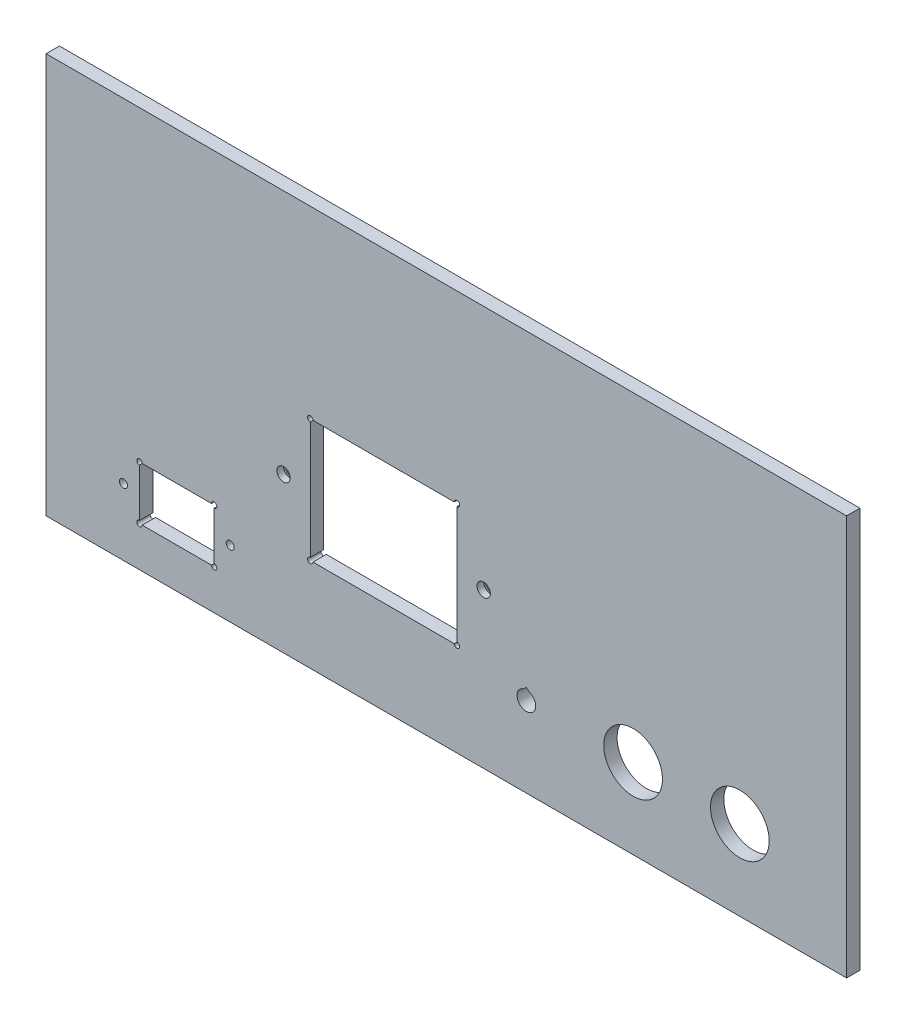
SolidWorks part; units mm, degrees
material "Glas"
ref_plane "Ebene vorne" through (0, 0, 0) normal (0, 0, 1) x (1, 0, 0)
ref_plane "Ebene oben" through (0, 0, 0) normal (0, 1, 0) x (1, 0, 0)
ref_plane "Ebene rechts" through (0, 0, 0) normal (1, 0, 0) x (0, 0, -1)
sketch "Skizze1" plane through (0, 0, 0) normal (0, 0, 1) x (1, 0, 0)
  line L1 (-150, 75) -> (150, 75)
  line L2 (-150, 75) -> (-150, -75)
  line L3 (-150, -75) -> (150, -75)
  line L4 (150, 75) -> (150, -75)
  line L5 (-150, 75) -> (150, -75) construction
  line L6 (-150, -75) -> (150, 75) construction
  point P0 (0, 0)
  dimension "D1" = 300
  dimension "D2" = 150
extrude "Aufsatz-Linear austragen1" add sketch "Skizze1" along normal blind 5
sketch "Skizze2" plane through (0, 0, 5) normal (0, 0, 1) x (1, 0, 0)
  line L0 (-150, 75) -> (-150, -75) construction
  line L1 (-115, -40) -> (-87, -40)
  line L2 (-115, -40) -> (-115, -60)
  line L3 (-115, -60) -> (-87, -60)
  line L4 (-87, -40) -> (-87, -60)
  line L5 (-115, -40) -> (-87, -60) construction
  line L6 (-115, -60) -> (-87, -40) construction
  line L7 (-150, -75) -> (150, -75) construction
  line L8 (-81, -50) -> (-121, -50) construction
  circle A0 centre (-121, -50) radius 1.5
  circle A1 centre (-81, -50) radius 1.5
  point P0 (-101, -50)
  point P12 (-101, -50)
  dimension "D6" = 3
  dimension "D1" = 28
  dimension "D2" = 20
  dimension "D3" = 35
  dimension "D4" = 15
  dimension "D5" = 40
extrude "Schnitt-Linear austragen1" cut sketch "Skizze2" against normal through all
sketch "Skizze3" plane through (0, 0, 5) normal (0, 0, 1) x (1, 0, 0)
  line L1 (70, -45) -> (110, -45) construction
  line L2 (150, -75) -> (150, 75) construction
  line L3 (-150, -75) -> (150, -75) construction
  circle A0 centre (110, -45) radius 11
  circle A1 centre (70, -45) radius 11
  dimension "D2" = 22
  dimension "D1" = 40
  dimension "D3" = 40
  dimension "D4" = 30
extrude "Schnitt-Linear austragen2" cut sketch "Skizze3" against normal through all
sketch "Skizze4" plane through (0, 0, 5) normal (0, 0, 1) x (1, 0, 0)
  circle A0 centre (-115, -40) radius 1
  circle A1 centre (-87, -40) radius 1
  circle A2 centre (-87, -60) radius 1
  circle A3 centre (-115, -60) radius 1
  dimension "D1" = 2
extrude "Schnitt-Linear austragen3" cut sketch "Skizze4" against normal through all
sketch "Skizze5" plane through (0, 0, 5) normal (0, 0, 1) x (1, 0, 0)
  line L0 (-114, -60) -> (-88, -60) construction
  line L1 (-51, -40) -> (4, -40)
  line L2 (-51, -40) -> (-51, 6)
  line L3 (-51, 6) -> (4, 6)
  line L4 (4, -40) -> (4, 6)
  line L5 (-51, -40) -> (4, 6) construction
  line L6 (-51, 6) -> (4, -40) construction
  line L7 (14, -17) -> (-61, -17) construction
  circle A0 centre (-81, -50) radius 1.5 construction
  circle A1 centre (-61, -17) radius 2.5
  circle A2 centre (14, -17) radius 2.5
  point P4 (-23.5, -17)
  point P12 (-23.5, -17)
  dimension "D5" = 5
  dimension "D1" = 55
  dimension "D2" = 46
  dimension "D3" = 20
  dimension "D4" = 30
  dimension "D6" = 10
extrude "Schnitt-Linear austragen4" cut sketch "Skizze5" against normal through all
sketch "Skizze6" plane through (0, 0, 5) normal (0, 0, 1) x (1, 0, 0)
  circle A0 centre (-51, 6) radius 1
  circle A1 centre (4, 6) radius 1
  circle A2 centre (4, -40) radius 1
  circle A3 centre (-51, -40) radius 1
  dimension "D1" = 2
extrude "Schnitt-Linear austragen5" cut sketch "Skizze6" against normal through all
sketch "Skizze7" plane through (0, 0, 5) normal (0, 0, 1) x (1, 0, 0)
  line L0 (30, -45) -> (110, -45) construction
  line L1 (30, -45) -> (30, -40.6459) construction
  line L2 (31, -48.3541) -> (29, -48.3541) construction
  line L3 (31, -48.3541) -> (31, -41.6459) construction
  line L4 (31, -41.6459) -> (29, -41.6459) construction
  line L5 (29, -48.3541) -> (29, -41.6459) construction
  line L6 (31, -48.3541) -> (29, -41.6459) construction
  line L7 (31, -41.6459) -> (29, -48.3541) construction
  line L8 (31, -41.6459) -> (30, -40.6459)
  line L9 (30, -40.6459) -> (29, -41.6459)
  circle A0 centre (30, -45) radius 3.5
  circle A1 centre (70, -45) radius 11 construction
  point P5 (70, -45)
  dimension "D1" = 7
  dimension "D2" = 2
  dimension "D3" = 1
extrude "Schnitt-Linear austragen6" cut sketch "Skizze7" against normal through all contours A0 L8 L9
chamfer "Fase1" distance 2.5 angle 45 2 edges at (-58.5, -17, 0) (16.5, -17, 0)
